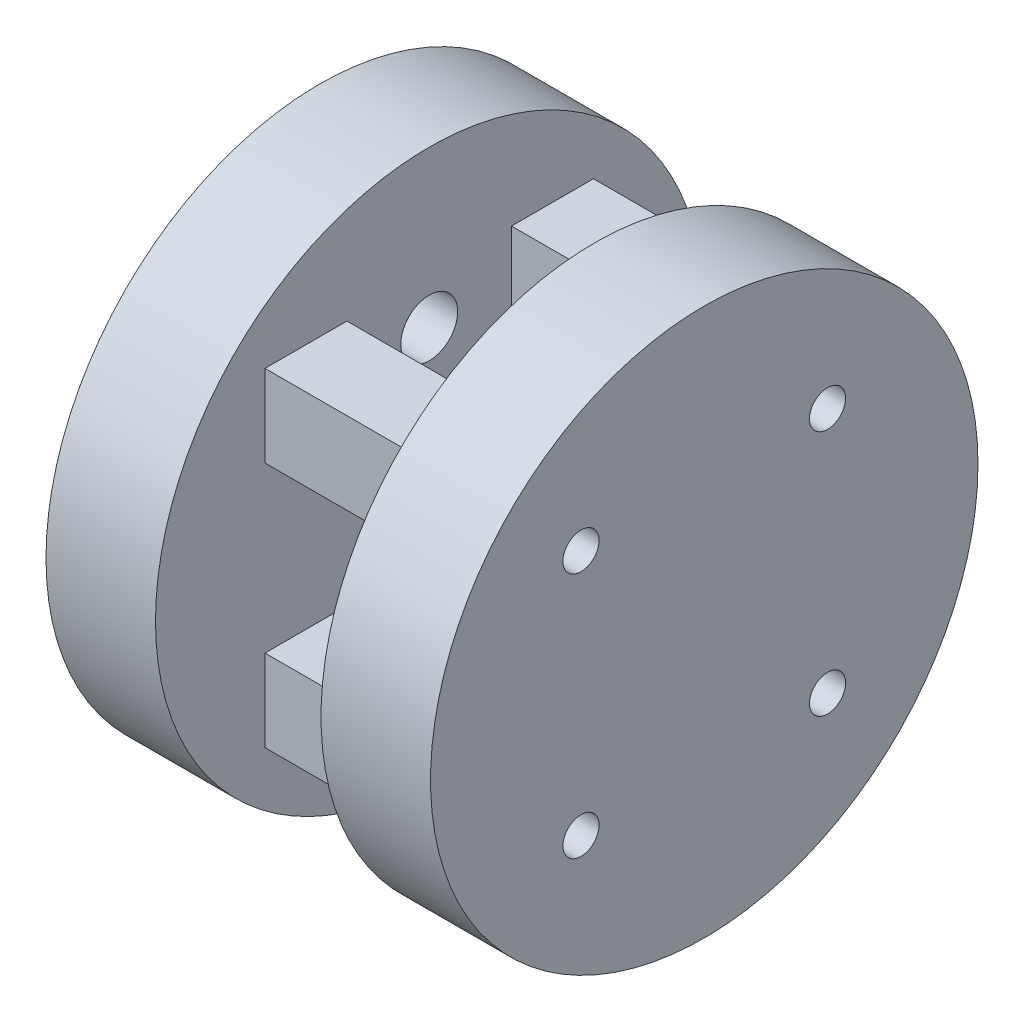
SolidWorks part; units mm, degrees
ref_plane "Front Plane" through (0, 0, 0) normal (0, 0, 1) x (1, 0, 0)
ref_plane "Top Plane" through (0, 0, 0) normal (0, 1, 0) x (1, 0, 0)
ref_plane "Right Plane" through (0, 0, 0) normal (1, 0, 0) x (0, 0, -1)
sketch "Sketch1" plane through (0, 0, 0) normal (1, 0, 0) x (0, 0, -1)
  line L1 (-15, 15) -> (15, 15)
  line L2 (-15, 15) -> (-15, -15)
  line L3 (-15, -15) -> (15, -15)
  line L4 (15, 15) -> (15, -15)
  line L5 (-15, 15) -> (15, -15) construction
  line L6 (-15, -15) -> (15, 15) construction
  point P0 (0, 0)
  dimension "D1" = 30
extrude "Boss-Extrude1" add sketch "Sketch1" along normal blind 10
sketch "Sketch2" plane through (10, 0, 0) normal (1, 0, 0) x (0, 0, -1)
  line L0 (-15, 15) -> (-15, 7.516)
  line L1 (-15, 15) -> (-15, -15) construction
  line L2 (-15, 7.516) -> (-7.516, 7.516)
  line L3 (-7.516, 7.516) -> (-7.516, 15)
  line L4 (15, 15) -> (-15, 15) construction
  line L5 (-7.516, 15) -> (-15, 15)
  line L6 (15, 15) -> (7.516, 15)
  line L7 (7.516, 15) -> (7.516, 7.516)
  line L8 (7.516, 7.516) -> (15, 7.516)
  line L9 (15, -15) -> (15, 15) construction
  line L10 (15, 7.516) -> (15, 15)
  line L11 (15, -15) -> (15, -7.516)
  line L12 (15, -7.516) -> (7.516, -7.516)
  line L13 (7.516, -7.516) -> (7.516, -15)
  line L14 (-15, -15) -> (15, -15) construction
  line L15 (7.516, -15) -> (15, -15)
  line L16 (-15, -15) -> (-7.516, -15)
  line L17 (-7.516, -15) -> (-7.516, -7.516)
  line L18 (-7.516, -7.516) -> (-15, -7.516)
  line L19 (-15, -7.516) -> (-15, -15)
  dimension "D1" = 15.032
  dimension "D2" = 15.032
extrude "Boss-Extrude2" add sketch "Sketch2" along normal blind 15.12
sketch "Sketch3" plane through (10, 0, 0) normal (1, 0, 0) x (0, 0, -1)
  line L0 (0, 10.7) -> (0, -10.7) construction
  circle A0 centre (0, 10.7) radius 2.5963
  circle A1 centre (0, -10.7) radius 2.5963
  circle A2 centre (0, 0) radius 2.5963
  point P4 (0, 0)
  dimension "D1" = 21.4
extrude "Cut-Extrude1" cut sketch "Sketch3" against normal through all
sketch "Sketch4" plane through (0, 0, 0) normal (-1, 0, 0) x (0, 0, 1)
  line L8 (-15, 15) -> (15, 15) construction
  line L9 (-15, 15) -> (15, 15)
  line L10 (15, 15) -> (15, -15) construction
  line L17 (15, -15) -> (-15, -15) construction
  line L24 (-15, -15) -> (-15, 15) construction
  line L25 (15, 15) -> (15, -15)
  line L26 (15, -15) -> (-15, -15)
  line L27 (-15, -15) -> (-15, 15)
  circle A9 centre (0, 0) radius 25
  dimension "D1" = 50
extrude "Boss-Extrude4" add sketch "Sketch4" against normal up to surface (10 mm away) up to face at (10, 10.7, -2.5963)
sketch "Sketch5" plane through (25.12, 0, 0) normal (1, 0, 0) x (0, 0, -1)
  circle A0 centre (0, 0) radius 25 construction
  circle A1 centre (0, 0) radius 25
extrude "Boss-Extrude5" add sketch "Sketch5" along normal blind 10 separate body
sketch "Sketch6" plane through (35.12, 0, 0) normal (1, 0, 0) x (0, 0, -1)
  line L0 (7.516, 15) -> (15, 15) construction
  line L1 (7.516, 15) -> (7.516, 7.516) construction
  line L2 (-15, 15) -> (-7.516, 15) construction
  line L3 (-15, 7.516) -> (-15, 15) construction
  line L4 (7.516, -7.516) -> (7.516, -15) construction
  line L5 (15, -7.516) -> (7.516, -7.516) construction
  line L6 (-7.516, -7.516) -> (-15, -7.516) construction
  line L7 (-15, -15) -> (-15, -7.516) construction
  line L8 (7.516, 15) -> (15, 15) construction
  line L9 (7.516, 15) -> (7.516, 7.516) construction
  line L10 (-15, 15) -> (-7.516, 15) construction
  line L11 (-15, 7.516) -> (-15, 15) construction
  line L12 (7.516, -7.516) -> (7.516, -15) construction
  line L13 (15, -7.516) -> (7.516, -7.516) construction
  line L14 (-7.516, -7.516) -> (-15, -7.516) construction
  line L15 (-15, -15) -> (-15, -7.516) construction
  line L16 (-15, 7.516) -> (-7.516, 15) construction
  line L17 (-15, -15) -> (-7.516, -7.516) construction
  line L18 (7.516, -15) -> (15, -7.516) construction
  line L19 (7.516, 7.516) -> (15, 15) construction
  circle A1 centre (-11.258, 11.258) radius 1.45
  circle A2 centre (-11.258, -11.258) radius 1.45
  circle A3 centre (11.258, -11.258) radius 1.45
  circle A4 centre (11.258, 11.258) radius 1.45
  dimension "D1" = 2.9
extrude "Cut-Extrude2" cut sketch "Sketch6" against normal blind 10
sketch "Sketch7" plane through (35.12, 0, 0) normal (1, 0, 0) x (0, 0, -1)
  circle A0 centre (11.258, 11.258) radius 1.45 construction
  circle A1 centre (11.258, -11.258) radius 1.65
  circle A2 centre (-11.258, -11.258) radius 1.45 construction
  circle A3 centre (-11.258, 11.258) radius 1.45 construction
  circle A4 centre (11.258, 11.258) radius 1.45 construction
  circle A6 centre (-11.258, -11.258) radius 1.45 construction
  circle A7 centre (-11.258, 11.258) radius 1.45 construction
  circle A8 centre (-11.258, 11.258) radius 1.65
  circle A9 centre (-11.258, -11.258) radius 1.65
  circle A11 centre (11.258, 11.258) radius 1.65
  dimension "D1" = 3.3
extrude "Cut-Extrude3" cut sketch "Sketch7" against normal through all
sketch "Sketch8" plane through (25.12, 0, 0) normal (1, 0, 0) x (0, 0, -1)
  circle A0 centre (-11.258, 11.258) radius 1.45
  circle A1 centre (-11.258, -11.258) radius 1.45
  circle A3 centre (11.258, 11.258) radius 1.45
  circle A4 centre (11.258, -11.258) radius 1.45
  dimension "D1" = 2.9
extrude "Cut-Extrude4" cut sketch "Sketch8" against normal blind 10
